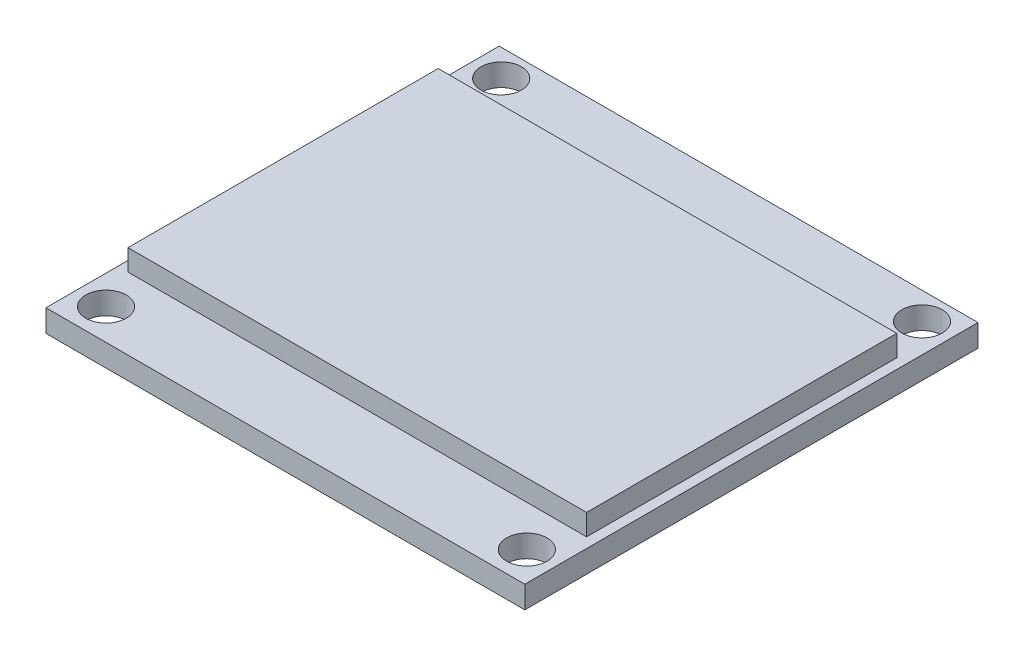
SolidWorks part; units mm, degrees
ref_plane "Front Plane" through (0, 0, 0) normal (0, 0, 1) x (1, 0, 0)
ref_plane "Top Plane" through (0, 0, 0) normal (0, 1, 0) x (1, 0, 0)
ref_plane "Right Plane" through (0, 0, 0) normal (1, 0, 0) x (0, 0, -1)
sketch "Sketch1" plane through (0, 0, 0) normal (0, 1, 0) x (1, 0, 0)
  line L1 (-16.8793, 11.9932) -> (18.6207, 11.9932)
  line L2 (-16.8793, 11.9932) -> (-16.8793, -21.6068)
  line L3 (-16.8793, -21.6068) -> (18.6207, -21.6068)
  line L4 (18.6207, 11.9932) -> (18.6207, -21.6068)
  circle A0 centre (-14.7293, 9.9932) radius 1.5
  circle A1 centre (16.4707, 9.9932) radius 1.5
  circle A2 centre (-14.7293, -19.3068) radius 1.5
  circle A3 centre (16.4707, -19.3068) radius 1.5
  dimension "D3" = 3
  dimension "D1" = 35.5
  dimension "D2" = 33.6
  dimension "D4" = 2.15
  dimension "D5" = 2
  dimension "D6" = 2
  dimension "D7" = 2.15
  dimension "D8" = 2.15
  dimension "D9" = 2.15
  dimension "D10" = 2.3
  dimension "D11" = 2.3
extrude "Boss-Extrude1" add sketch "Sketch1" along normal blind 1.65
sketch "Sketch2" plane through (0, 1.65, 0) normal (0, 1, 0) x (1, 0, 0)
  line L0 (0.8707, 13.2037) -> (0.8707, -23.7771) construction
  line L1 (-16.1293, 6.7232) -> (17.8707, 6.7232)
  line L2 (-16.1293, 6.7232) -> (-16.1293, -16.2768)
  line L3 (-16.1293, -16.2768) -> (17.8707, -16.2768)
  line L4 (17.8707, 6.7232) -> (17.8707, -16.2768)
  line L5 (-16.8793, 11.9932) -> (-16.8793, -21.6068) construction
  line L6 (18.6207, -21.6068) -> (18.6207, 11.9932) construction
  line L7 (18.6207, 11.9932) -> (-16.8793, 11.9932) construction
  line L8 (-16.8793, -21.6068) -> (18.6207, -21.6068) construction
  dimension "D1" = 23
  dimension "D2" = 34
  dimension "D3" = 5.27
  dimension "D4" = 5.33
extrude "Boss-Extrude2" add sketch "Sketch2" along normal blind 1.57
